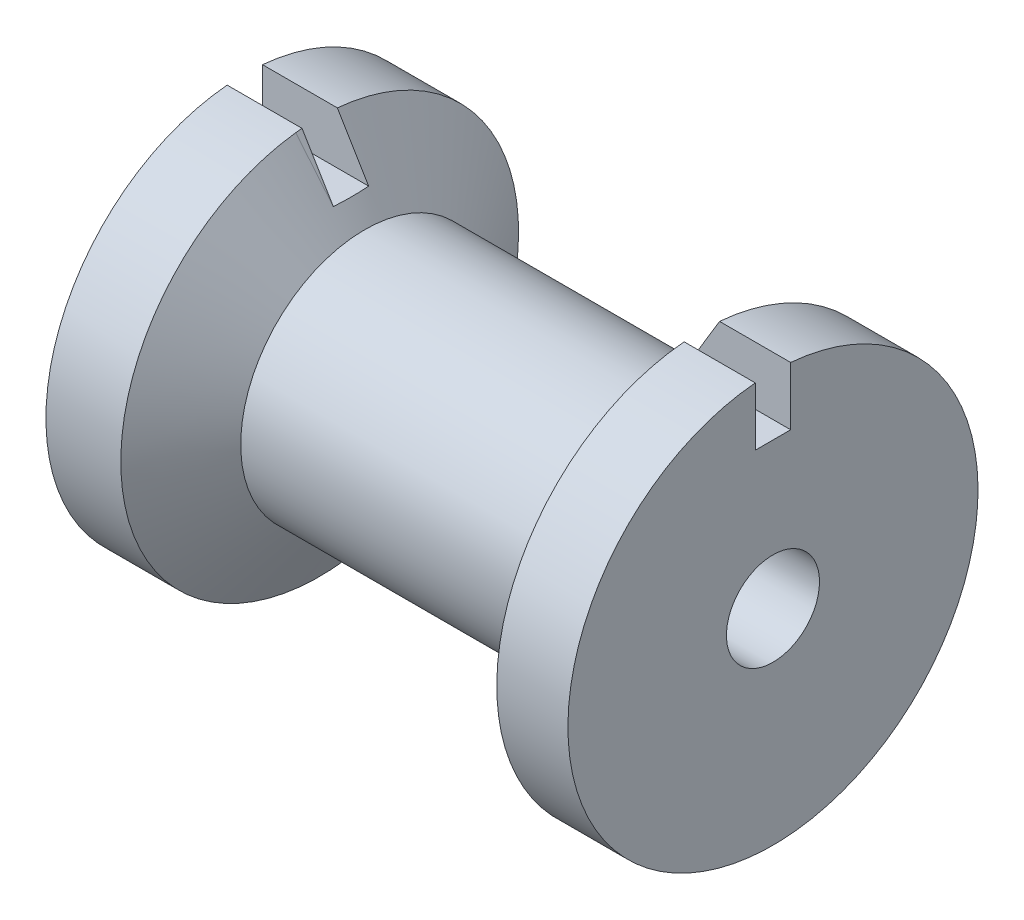
SolidWorks part; units mm, degrees
ref_plane "Front Plane" through (0, 0, 0) normal (0, 0, 1) x (1, 0, 0)
ref_plane "Top Plane" through (0, 0, 0) normal (0, 1, 0) x (1, 0, 0)
ref_plane "Right Plane" through (0, 0, 0) normal (1, 0, 0) x (0, 0, -1)
sketch "Sketch1" plane through (0, 0, 0) normal (0, 0, 1) x (1, 0, 0)
  line L1 (-12.3858, 10.6691) -> (-16.2661, 17.0976)
  line L2 (-12.3858, 10.6691) -> (12.3858, 10.6691)
  line L3 (16.5859, 17.6273) -> (22.7017, 17.6273)
  line L4 (22.7017, 17.6273) -> (22.7017, 0)
  line L5 (22.7017, 0) -> (-22.7017, 0)
  line L6 (-22.7017, 17.0976) -> (-22.7017, 0)
  line L7 (-16.2661, 17.0976) -> (-22.7017, 17.0976)
  line L8 (12.3858, 10.6691) -> (16.5859, 17.6273)
revolve "Revolve2" add sketch "Sketch1" angle 360 about L5
sketch "Sketch2" plane through (22.7017, 0, 0) normal (1, 0, 0) x (0, 0, -1)
  line L1 (-1.5211, 22.705) -> (1.5211, 22.705)
  line L2 (-1.5211, 22.705) -> (-1.5211, 12.5497)
  line L3 (-1.5211, 12.5497) -> (1.5211, 12.5497)
  line L4 (1.5211, 22.705) -> (1.5211, 12.5497)
  line L5 (-1.5211, 22.705) -> (1.5211, 12.5497) construction
  line L6 (-1.5211, 12.5497) -> (1.5211, 22.705) construction
  circle A0 centre (0, 0) radius 4
  circle A1 centre (0, 0) radius 17.6273 construction
  point P3 (0, 17.6273)
extrude "Cut-Extrude1" cut sketch "Sketch2" against normal through all
